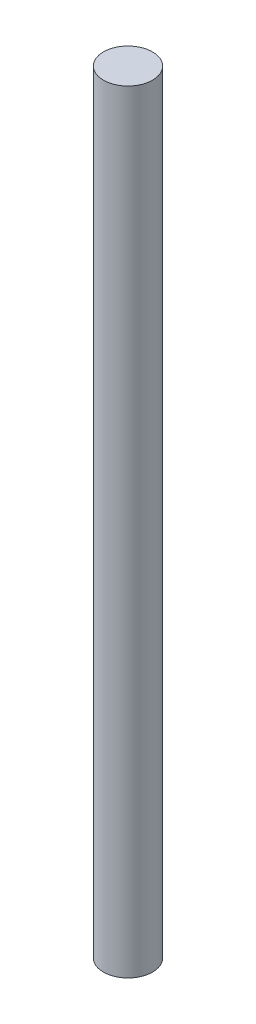
SolidWorks part; units mm, degrees
ref_plane "Front Plane" through (0, 0, 0) normal (0, 0, 1) x (1, 0, 0)
ref_plane "Top Plane" through (0, 0, 0) normal (0, 1, 0) x (1, 0, 0)
ref_plane "Right Plane" through (0, 0, 0) normal (1, 0, 0) x (0, 0, -1)
sketch "Sketch1" plane through (0, 0, 0) normal (0, 1, 0) x (1, 0, 0)
  circle A0 centre (0, 0) radius 9.525
  dimension "D1" = 19.05
extrude "Boss-Extrude1" add sketch "Sketch1" along normal blind 300
